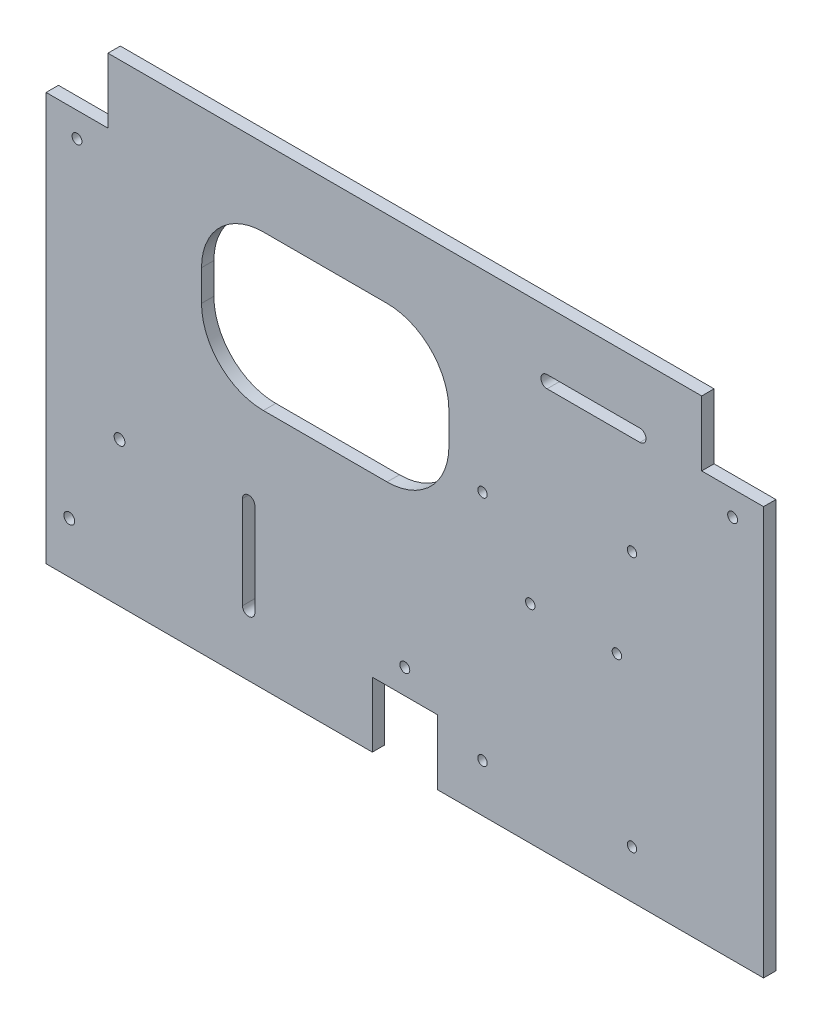
SolidWorks part; units mm, degrees
ref_plane "Front Plane" through (0, 0, 0) normal (0, 0, 1) x (1, 0, 0)
ref_plane "Top Plane" through (0, 0, 0) normal (0, 1, 0) x (1, 0, 0)
ref_plane "Right Plane" through (0, 0, 0) normal (1, 0, 0) x (0, 0, -1)
sketch "Sketch1" plane through (0, 0, 0) normal (0, 0, 1) x (1, 0, 0)
  line L1 (-116, 85) -> (116, 85)
  line L2 (-116, 85) -> (-116, -85)
  line L3 (-116, -85) -> (116, -85)
  line L4 (116, 85) -> (116, -85)
  line L5 (-116, 85) -> (116, -85) construction
  line L6 (-116, -85) -> (116, 85) construction
  point P0 (0, 0)
  dimension "D1" = 232
  dimension "D2" = 170
extrude "Boss-Extrude1" add sketch "Sketch1" along normal blind 4
sketch "Sketch4" plane through (0, 0, 4) normal (0, 0, 1) x (1, 0, 0)
  line L0 (0, -2.2) -> (0, 2.2) construction
  line L1 (-116, -85) -> (-81, -85)
  line L2 (-116, -85) -> (-116, -20)
  line L3 (-116, -20) -> (-81, -20)
  line L4 (-81, -85) -> (-81, -20)
  line L5 (81, -85) -> (81, -20)
  line L6 (116, -20) -> (81, -20)
  line L7 (116, -85) -> (116, -20)
  line L8 (116, -85) -> (81, -85)
  dimension "D1" = 35
  dimension "D2" = 65
extrude "Cut-Extrude3" [suppressed] cut sketch "Sketch4" against normal through all
sketch "Sketch5" plane through (0, 0, 4) normal (0, 0, 1) x (1, 0, 0)
  line L12 (-45.7396, -1.949) -> (-5.7396, -1.949)
  line L13 (-65.7396, 18.051) -> (-65.7396, 28.051)
  line L14 (-45.7396, 48.051) -> (-5.7396, 48.051)
  line L15 (14.2604, 18.051) -> (14.2604, 28.051)
  arc A0 (-5.7396, 48.051) -> (14.2604, 28.051) centre (-5.7396, 28.051) cw
  arc A1 (-65.7396, 28.051) -> (-45.7396, 48.051) centre (-45.7396, 28.051) cw
  arc A2 (-45.7396, -1.949) -> (-65.7396, 18.051) centre (-45.7396, 18.051) cw
  arc A3 (-5.7396, -1.949) -> (14.2604, 18.051) centre (-5.7396, 18.051) ccw
  point P8 (-65.7396, 48.051)
  point P11 (-65.7396, -1.949)
  point P14 (14.2604, -1.949)
  dimension "D3" = 20
  dimension "D1" = 80
  dimension "D2" = 50
extrude "Cut-Extrude4" cut sketch "Sketch5" against normal through all
sketch "Sketch6" plane through (0, 0, 4) normal (0, 0, 1) x (1, 0, 0)
  circle A0 centre (73.46, 18.0986) radius 1.5234
  circle A1 centre (25.1238, 10.6056) radius 1.5234
  circle A2 centre (68.5815, -12.9021) radius 1.5234
  circle A3 centre (40.5653, -12.9021) radius 1.5234
  circle A4 centre (73.46, -64.5276) radius 1.5234
  circle A5 centre (25.1238, -64.5276) radius 1.5234
extrude "Cut-Extrude5" cut sketch "Sketch6" against normal through all
sketch "Sketch7" [suppressed] plane through (0, 0, 4) normal (0, 0, 1) x (1, 0, 0)
  line L0 (81, -20) -> (81, -85) construction
  line L1 (-81, -85) -> (81, -85)
  line L2 (-81, -85) -> (-81, -81)
  line L3 (-81, -81) -> (81, -81)
  line L4 (81, -85) -> (81, -81)
  line L5 (-116, 53.1172) -> (-116, -20) construction
  line L6 (116, -20) -> (116, 53.1172) construction
  line L7 (-116, 85) -> (116, 85)
  line L8 (-116, 85) -> (-116, 81)
  line L9 (-116, 81) -> (116, 81)
  line L10 (116, 85) -> (116, 81)
  line L11 (116, -20) -> (116, 53.1172) construction
  dimension "D1" = 4
  dimension "D2" = 4
extrude "Cut-Extrude6" [suppressed] cut sketch "Sketch7" against normal through all
fillet "Fillet1" [suppressed] radius 4
fillet "Fillet2" [suppressed] radius 4
sketch "Sketch8" plane through (0, 0, 4) normal (0, 0, 1) x (1, 0, 0)
  line L0 (116, -85) -> (116, 85) construction
  line L1 (-116, -85) -> (116, -85)
  line L2 (-116, -85) -> (-116, -80)
  line L3 (-116, -80) -> (116, -80)
  line L4 (116, -85) -> (116, -80)
  dimension "D1" = 5
extrude "Cut-Extrude7" cut sketch "Sketch8" against normal through all
sketch "Sketch9" plane through (0, 0, 0) normal (0, 0, -1) x (-1, 0, 0)
  circle A0 centre (106, 44) radius 1.6
  circle A1 centre (-106, 44) radius 1.6
  circle A2 centre (0, -51) radius 1.6
  dimension "D1" = 3.2
  dimension "D2" = 3.2
  dimension "D3" = 3.2
extrude "Cut-Extrude8" cut sketch "Sketch9" against normal through all
sketch "Sketch10" plane through (0, 0, 4) normal (0, 0, 1) x (1, 0, 0)
  circle A0 centre (-92.25, -33.3) radius 1.75
  circle A1 centre (-108.5, -63.5) radius 1.75
  dimension "D1" = 3.5
  dimension "D2" = 3.5
extrude "Cut-Extrude9" cut sketch "Sketch10" against normal through all
sketch "Sketch11" plane through (0, 0, 4) normal (0, 0, 1) x (1, 0, 0)
  line L1 (116, 85) -> (96, 85)
  line L2 (116, 85) -> (116, 52)
  line L3 (116, 52) -> (96, 52)
  line L4 (96, 85) -> (96, 52)
  dimension "D1" = 20
  dimension "D2" = 33
extrude "Cut-Extrude10" cut sketch "Sketch11" against normal through all
ref_plane "Plane1" through (0, 0, 0) normal (-1, 0, 0) x (0, 0, 1)
mirror "Mirror1" about plane through (0, 0, 0) normal (-1, 0, 0) of "Cut-Extrude10"
sketch "Sketch12" plane through (0, 0, 4) normal (0, 0, 1) x (1, 0, 0)
  line L0 (0, 2.2) -> (0, -2.2) construction
  line L1 (-10.5, -80) -> (10.5, -80)
  line L2 (-10.5, -80) -> (-10.5, -59)
  line L3 (-10.5, -59) -> (10.5, -59)
  line L4 (10.5, -80) -> (10.5, -59)
  line L5 (116, -80) -> (-116, -80) construction
  point P4 (0, -80)
  dimension "D1" = 21
  dimension "D2" = 21
extrude "Cut-Extrude11" cut sketch "Sketch12" against normal blind 4
sketch "Sketch13" plane through (0, 0, 4) normal (0, 0, 1) x (1, 0, 0)
  line L0 (-50.5, -30) -> (-50.5, -60) construction
  line L1 (-48.5, -30) -> (-48.5, -60)
  line L2 (-52.5, -30) -> (-52.5, -60)
  line L3 (46, 52) -> (76, 52) construction
  line L4 (46, 54) -> (76, 54)
  line L5 (46, 50) -> (76, 50)
  line L6 (-10.5, -80) -> (-116, -80) construction
  line L7 (-10.5, -59) -> (-10.5, -80) construction
  line L8 (96, 52) -> (116, 52) construction
  line L9 (96, 85) -> (96, 52) construction
  arc A0 (-48.5, -30) -> (-52.5, -30) centre (-50.5, -30) ccw
  arc A1 (-52.5, -60) -> (-48.5, -60) centre (-50.5, -60) ccw
  arc A2 (46, 54) -> (46, 50) centre (46, 52) ccw
  arc A3 (76, 50) -> (76, 54) centre (76, 52) ccw
  point P2 (-50.5, -45)
  point P7 (61, 52)
  dimension "D1" = 2
  dimension "D5" = 2
  dimension "D2" = 30
  dimension "D3" = 20
  dimension "D4" = 40
  dimension "D6" = 20
  dimension "D7" = 30
extrude "Cut-Extrude12" cut sketch "Sketch13" against normal blind 4
sketch "Sketch14" plane through (0, 0, 4) normal (0, 0, 1) x (1, 0, 0)
  line L0 (96, 85) -> (96, 52) construction
  line L1 (-96, 85) -> (96, 85)
  line L2 (-96, 85) -> (-96, 73)
  line L3 (-96, 73) -> (96, 73)
  line L4 (96, 85) -> (96, 73)
  dimension "D1" = 12
extrude "Cut-Extrude13" cut sketch "Sketch14" against normal blind 4
